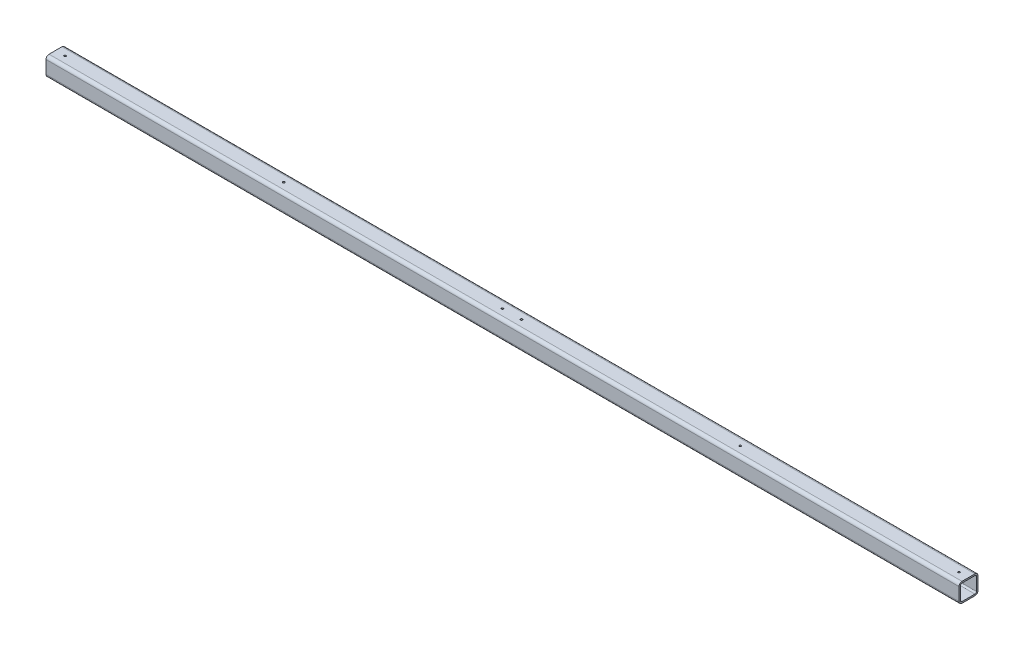
SolidWorks part; units mm, degrees
ref_plane "Front Plane" through (0, 0, 0) normal (0, 0, 1) x (1, 0, 0)
ref_plane "Top Plane" through (0, 0, 0) normal (0, 1, 0) x (1, 0, 0)
ref_plane "Right Plane" through (0, 0, 0) normal (1, 0, 0) x (0, 0, -1)
sketch "Sketch1" plane through (0, 0, 0) normal (0, 1, 0) x (1, 0, 0)
  line L0 (0, 0) -> (1920, 0)
  dimension "D1" = 1920
other "Tube (square) 40 X 40 X 3.2(4)"
ref_plane "Plane1" through (0, 0, 0) normal (1, 0, 0) x (0, 0, -1)
sketch "Sketch12" plane through (0, 0, 0) normal (1, 0, 0) x (0, 0, -1)
  line L0 (-13.6, -16.8) -> (13.6, -16.8)
  line L1 (-16.8, -13.6) -> (-16.8, 13.6)
  line L2 (13.6, 16.8) -> (-13.6, 16.8)
  line L3 (16.8, 13.6) -> (16.8, -13.6)
  line L4 (-13.6, -20) -> (13.6, -20)
  line L5 (-20, -13.6) -> (-20, 13.6)
  line L6 (13.6, 20) -> (-13.6, 20)
  line L7 (20, 13.6) -> (20, -13.6)
  line L8 (-20, 0) -> (-16.8, 0) construction
  line L9 (-16.8, 0) -> (16.8, 0) construction
  line L10 (16.8, 0) -> (20, 0) construction
  line L12 (0, 20) -> (0, 16.8) construction
  line L13 (0, 16.8) -> (0, -16.8) construction
  line L14 (0, -16.8) -> (0, -20) construction
  arc A0 (20, 13.6) -> (13.6, 20) centre (13.6, 13.6) ccw
  arc A1 (13.6, -20) -> (20, -13.6) centre (13.6, -13.6) ccw
  arc A2 (-20, -13.6) -> (-13.6, -20) centre (-13.6, -13.6) ccw
  arc A3 (-13.6, 20) -> (-20, 13.6) centre (-13.6, 13.6) ccw
  arc A4 (-13.6, 16.8) -> (-16.8, 13.6) centre (-13.6, 13.6) ccw
  arc A5 (16.8, 13.6) -> (13.6, 16.8) centre (13.6, 13.6) ccw
  arc A6 (13.6, -16.8) -> (16.8, -13.6) centre (13.6, -13.6) ccw
  arc A7 (-16.8, -13.6) -> (-13.6, -16.8) centre (-13.6, -13.6) ccw
  point P2 (-20, 20)
  point P33 (-20, -20)
  point P34 (20, -20)
  point P36 (20, 20)
  point P37 (0, 0)
  dimension "D1" = 6.4
  dimension "Thickness" = 3.2
  dimension "V_leg" = 40
  dimension "H_leg" = 40
ref_plane "Plane2" through (0, 20, 0) normal (0, 1, 0) x (1, 0, 0)
sketch "Sketch13" plane through (0, 20, 0) normal (0, 1, 0) x (1, 0, 0)
  line L0 (1900, -13.6) -> (1900, 13.6) construction
  line L1 (20, 13.6) -> (20, -13.6) construction
  line L2 (960, -13.6) -> (960, 13.6) construction
  line L3 (980, -13.6) -> (980, 13.6) construction
  line L4 (0, 13.6) -> (0, -13.6)
  line L5 (0, -13.6) -> (1920, -13.6)
  line L6 (1920, -13.6) -> (1920, 13.6)
  line L7 (1920, 13.6) -> (0, 13.6)
  line L8 (0, 13.6) -> (0, -13.6) construction
  line L9 (0, -13.6) -> (1920, -13.6) construction
  line L10 (1920, -13.6) -> (1920, 13.6) construction
  line L11 (1920, 13.6) -> (0, 13.6) construction
  line L12 (940, -13.6) -> (940, 13.6) construction
  line L13 (940, 0) -> (20, 0) construction
  line L14 (1900, 0) -> (980, 0) construction
  circle A0 centre (20, 0) radius 2
  circle A1 centre (1900, 0) radius 2
  circle A2 centre (980, 0) radius 2
  circle A3 centre (940, 0) radius 2
  circle A4 centre (1440, 0) radius 2
  circle A5 centre (480, 0) radius 2
  dimension "D1" = 0
extrude "Cut-Extrude1" cut sketch "Sketch13" against normal blind 3
